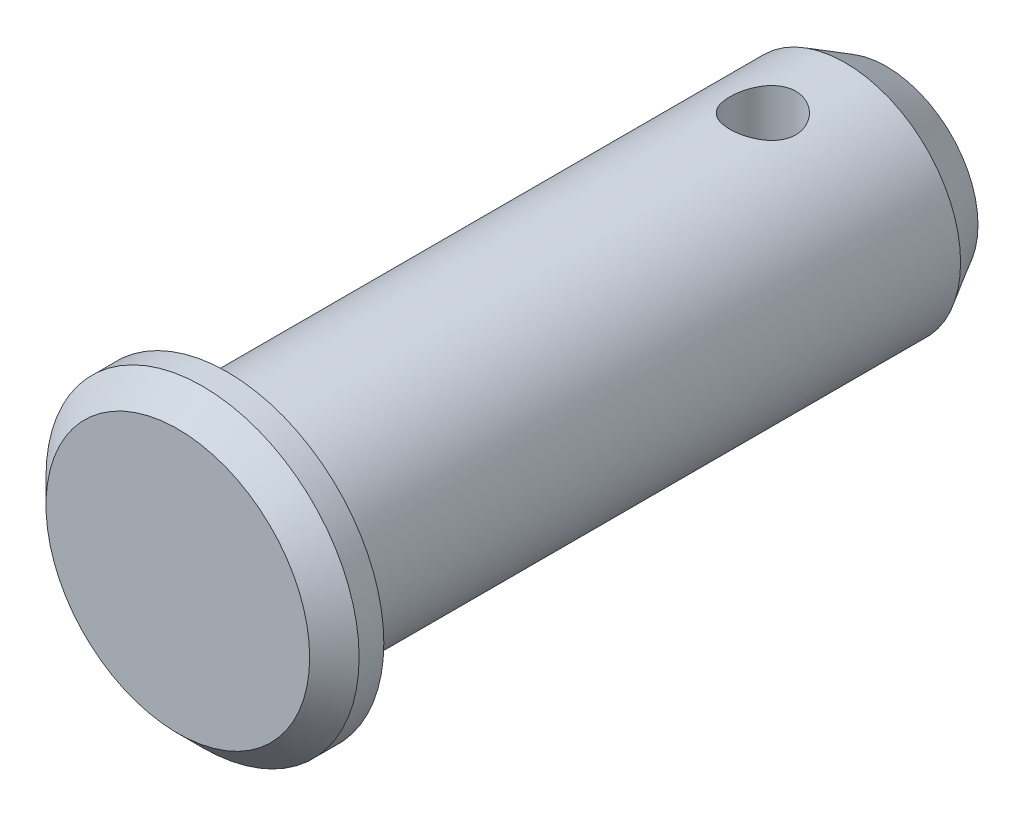
SolidWorks part; units mm, degrees
material "1.0545 (S355N)"
ref_plane "Płaszczyzna przednia" through (0, 0, 0) normal (0, 0, 1) x (1, 0, 0)
ref_plane "Płaszczyzna górna" through (0, 0, 0) normal (0, 1, 0) x (1, 0, 0)
ref_plane "Płaszczyzna prawa" through (0, 0, 0) normal (1, 0, 0) x (0, 0, -1)
sketch "Szkic1" plane through (0, 0, 0) normal (0, 1, 0) x (1, 0, 0)
  line L0 (8, -21.5) -> (-8, -21.5)
  line L1 (-9.5, -20) -> (-9.5, -18.5)
  line L2 (-9.5, -18.5) -> (-7, -18.5)
  line L3 (-7, -18.5) -> (-7, 19)
  line L4 (-5.5566, 21.5) -> (5.5566, 21.5)
  line L5 (7, 19) -> (7, -18.5)
  line L6 (7, -18.5) -> (9.5, -18.5)
  line L7 (9.5, -18.5) -> (9.5, -20)
  line L8 (9.5, -20) -> (8, -21.5)
  line L9 (-8, -21.5) -> (-9.5, -20)
  line L10 (5.5566, 21.5) -> (7, 19)
  line L11 (-7, 19) -> (-5.5566, 21.5)
  line L12 (0, -21.5) -> (0, 21.5)
  point P0 (9.5, -21.5)
  point P1 (-9.5, -21.5)
  point P5 (-7, 21.5)
  point P6 (7, 21.5)
  point P7 (0, 0)
  point P17 (0, 21.5)
  point P19 (0, -21.5)
  dimension "D1" = 19
  dimension "D2" = 14
  dimension "D3" = 2.5
  dimension "D4" = 30
  dimension "D8" = 30
  dimension "D9" = 40
  dimension "D10" = 3
revolve "Obrót1" add sketch "Szkic1" angle 360 about L12
sketch "Szkic2" plane through (0, 0, 0) normal (0, 1, 0) x (1, 0, 0)
  line L0 (7, -18.5) -> (-7, -18.5) construction
  circle A0 centre (0, 14) radius 2
  dimension "D2" = 4
  dimension "D1" = 32.5
extrude "Wytnij-wyciągnięcie1" cut sketch "Szkic2" against normal through all both and the other way through all contours A0
